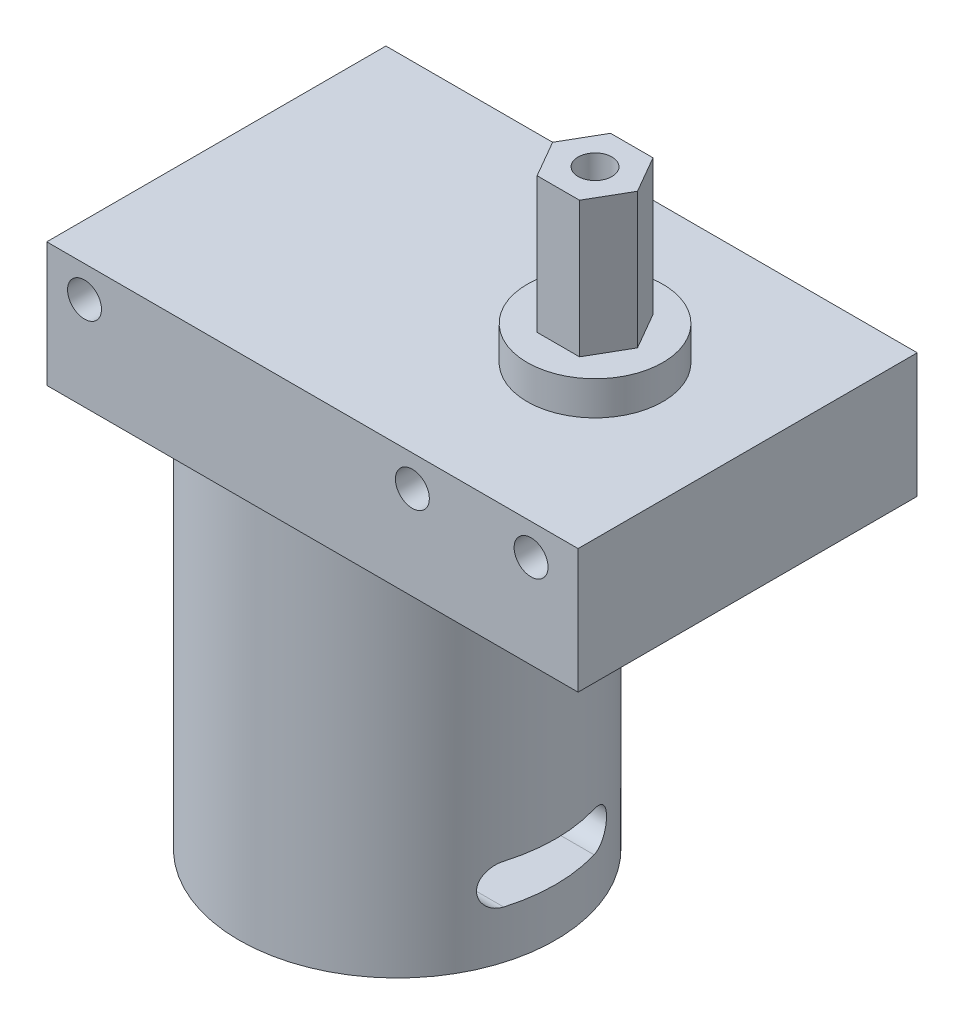
SolidWorks part; units mm, degrees
material "商用纯 CP-Ti UNS R50400 (SS)"
ref_plane "前视基准面" through (0, 0, 0) normal (0, 0, 1) x (1, 0, 0)
ref_plane "上视基准面" through (0, 0, 0) normal (0, 1, 0) x (1, 0, 0)
ref_plane "右视基准面" through (0, 0, 0) normal (1, 0, 0) x (0, 0, -1)
sketch "草图1" plane through (0, 0, 0) normal (0, 1, 0) x (1, 0, 0)
  line L1 (0, 0) -> (47, 0)
  line L2 (0, 0) -> (0, -30)
  line L3 (0, -30) -> (47, -30)
  line L4 (47, 0) -> (47, -30)
  dimension "D1" = 47
  dimension "D2" = 30
extrude "凸台-拉伸1" add sketch "草图1" along normal blind 11
sketch "草图2" plane through (0, 11, 0) normal (0, 1, 0) x (1, 0, 0)
  line L0 (47, 0) -> (0, 0) construction
  line L1 (47, -30) -> (47, 0) construction
  circle A0 centre (33.5, -15) radius 6
  dimension "D1" = 15
  dimension "D3" = 12
  dimension "D2" = 13.5
extrude "凸台-拉伸2" add sketch "草图2" along normal blind 3
sketch "草图3" plane through (0, 14, 0) normal (0, 1, 0) x (1, 0, 0)
  line L1 (37.2528, -15) -> (35.3764, -11.75)
  line L2 (35.3764, -11.75) -> (31.6236, -11.75)
  line L3 (31.6236, -11.75) -> (29.7472, -15)
  line L4 (29.7472, -15) -> (31.6236, -18.25)
  line L5 (31.6236, -18.25) -> (35.3764, -18.25)
  line L6 (35.3764, -18.25) -> (37.2528, -15)
  circle A0 centre (33.5, -15) radius 3.25 construction
  dimension "D1" = 6.5
extrude "凸台-拉伸3" add sketch "草图3" along normal blind 12
sketch "草图4" plane through (0, 0, 0) normal (0, -1, 0) x (1, 0, 0)
  line L0 (0, 30) -> (47, 30) construction
  line L1 (0, 0) -> (0, 30) construction
  circle A0 centre (16, 15) radius 14
  dimension "D1" = 15
  dimension "D3" = 28
  dimension "D2" = 16
extrude "凸台-拉伸4" add sketch "草图4" along normal blind 35
sketch "草图5" plane through (0, -35, 0) normal (0, -1, 0) x (1, 0, 0)
  circle A0 centre (16, 15) radius 5
  dimension "D1" = 10
extrude "凸台-拉伸5" add sketch "草图5" along normal blind 2
sketch "草图6" plane through (0, 0, 30) normal (0, 0, 1) x (1, 0, 0)
  line L0 (0, 11) -> (47, 11) construction
  circle A0 centre (3.3408, 8.25) radius 1.5
  circle A1 centre (32.3408, 8.25) radius 1.5
  circle A2 centre (42.8408, 8.25) radius 1.5
  dimension "D1" = 3
  dimension "D2" = 39.5
  dimension "D3" = 10.5
  dimension "D4" = 2.75
extrude "切除-拉伸1" cut sketch "草图6" against normal through all
sketch "草图7" plane through (0, 0, 0) normal (-1, 0, 0) x (0, 0, 1)
  line L0 (15, 11) -> (15, -29) construction
  line L1 (0, 11) -> (30, 11) construction
  line L2 (-10.279, -29) -> (39.7397, -29) construction
  line L3 (11, -29) -> (19, -29) construction
  line L4 (11, -27.25) -> (19, -27.25)
  line L5 (11, -30.75) -> (19, -30.75)
  arc A0 (11, -27.25) -> (11, -30.75) centre (11, -29) ccw
  arc A1 (19, -30.75) -> (19, -27.25) centre (19, -29) ccw
  point P8 (15, -29)
  dimension "D1" = 3.5
  dimension "D2" = 8
extrude "切除-拉伸2" cut sketch "草图7" against normal through all
sketch "草图9" plane through (0, 26, 0) normal (0, 1, 0) x (1, 0, 0)
  circle A0 centre (33.5, -15) radius 1.5
extrude "切除-拉伸3" cut sketch "草图9" against normal blind 8
sketch "草图11" plane through (0, -37, 0) normal (0, -1, 0) x (1, 0, 0)
  circle A0 centre (16, 15) radius 0.5
